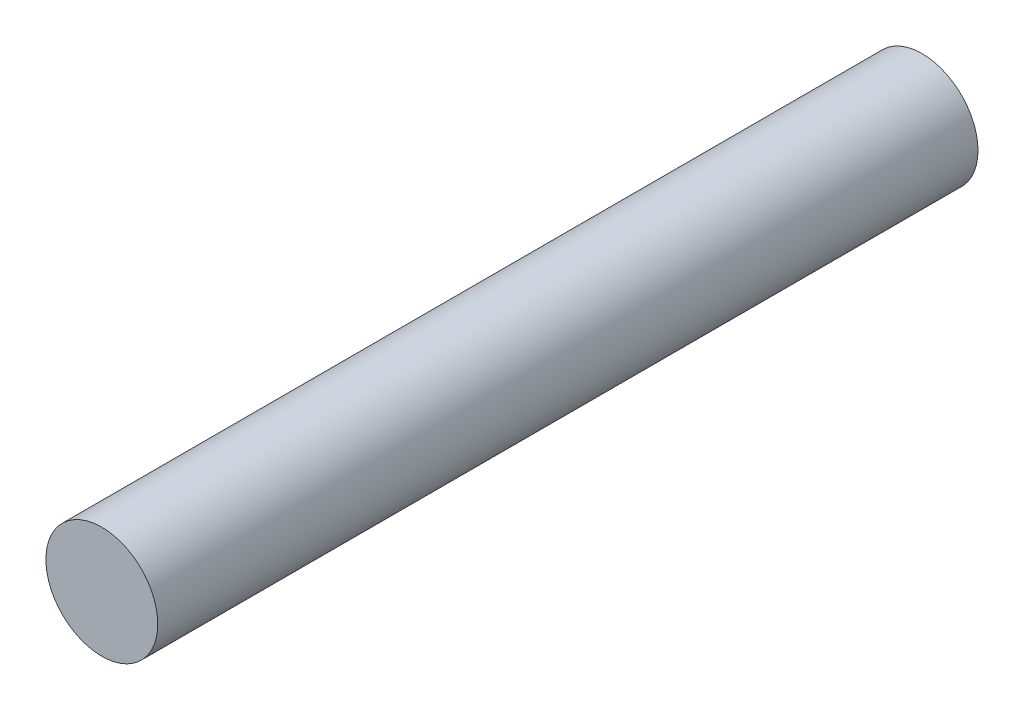
SolidWorks part; units mm, degrees
ref_plane "Plan de face" through (0, 0, 0) normal (0, 0, 1) x (1, 0, 0)
ref_plane "Plan de dessus" through (0, 0, 0) normal (0, 1, 0) x (1, 0, 0)
ref_plane "Plan de droite" through (0, 0, 0) normal (1, 0, 0) x (0, 0, -1)
sketch "Esquisse1" plane through (0, 0, 0) normal (0, 0, 1) x (1, 0, 0)
  circle A0 centre (0, 0) radius 15
  dimension "D1" = 30
extrude "Boss.-Extru.1" add sketch "Esquisse1" along normal blind 220
